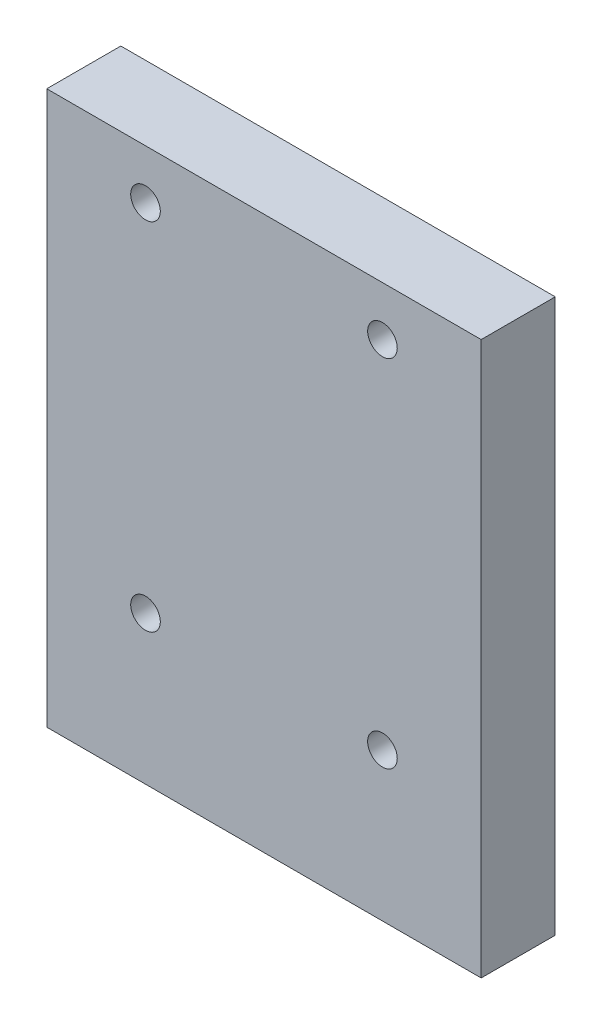
SolidWorks part; units mm, degrees
ref_plane "前基準面" through (0, 0, 0) normal (0, 0, 1) x (1, 0, 0)
ref_plane "上基準面" through (0, 0, 0) normal (0, 1, 0) x (1, 0, 0)
ref_plane "右基準面" through (0, 0, 0) normal (1, 0, 0) x (0, 0, -1)
sketch "草圖1" plane through (0, 0, 0) normal (0, 0, 1) x (1, 0, 0)
  line L0 (0, 0) -> (0, 23) construction
  line L1 (-12, 18) -> (12, 18) construction
  line L2 (-12, 18) -> (-12, -18) construction
  line L3 (-12, -18) -> (12, -18) construction
  line L4 (12, 18) -> (12, -18) construction
  line L5 (-12, 18) -> (12, -18) construction
  line L6 (-12, -18) -> (12, 18) construction
  line L7 (-22, 23) -> (22, 23)
  line L8 (-22, 23) -> (-22, -33)
  line L9 (-22, -33) -> (22, -33)
  line L10 (22, 23) -> (22, -33)
  circle A2 centre (-12, 18) radius 1.5
  circle A3 centre (12, 18) radius 1.5
  circle A4 centre (12, -18) radius 1.5
  circle A5 centre (-12, -18) radius 1.5
  point P0 (0, 0)
  point P6 (0, 0)
  dimension "D5" = 23
  dimension "D7" = 3
  dimension "D1" = 24
  dimension "D2" = 36
  dimension "D3" = 44
  dimension "D4" = 33
extrude "填料-伸長1" add sketch "草圖1" along normal blind 7.5
ref_plane "平面1" through (0, -33, 0) normal (0, -1, 0) x (-1, 0, 0)
sketch "草圖2" plane through (0, -33, 0) normal (0, -1, 0) x (-1, 0, 0)
  line L0 (0, 0) -> (0, -3.75)
  line L1 (0, -3.75) -> (-6, -3.75)
  line L2 (-6, -3.75) -> (-18, -3.75)
  line L3 (0, -3.75) -> (6, -3.75)
  line L4 (6, -3.75) -> (18, -3.75)
  circle A0 centre (-6, -3.75) radius 1.5
  circle A1 centre (-18, -3.75) radius 1.5
  circle A2 centre (6, -3.75) radius 1.5
  circle A3 centre (18, -3.75) radius 1.5
  dimension "D1" = 3
  dimension "D2" = 3.75
  dimension "D3" = 6
  dimension "D4" = 12
extrude "除料-伸長1" cut sketch "草圖2" against normal blind 3 contours A3 | A2 | A0 | A1
